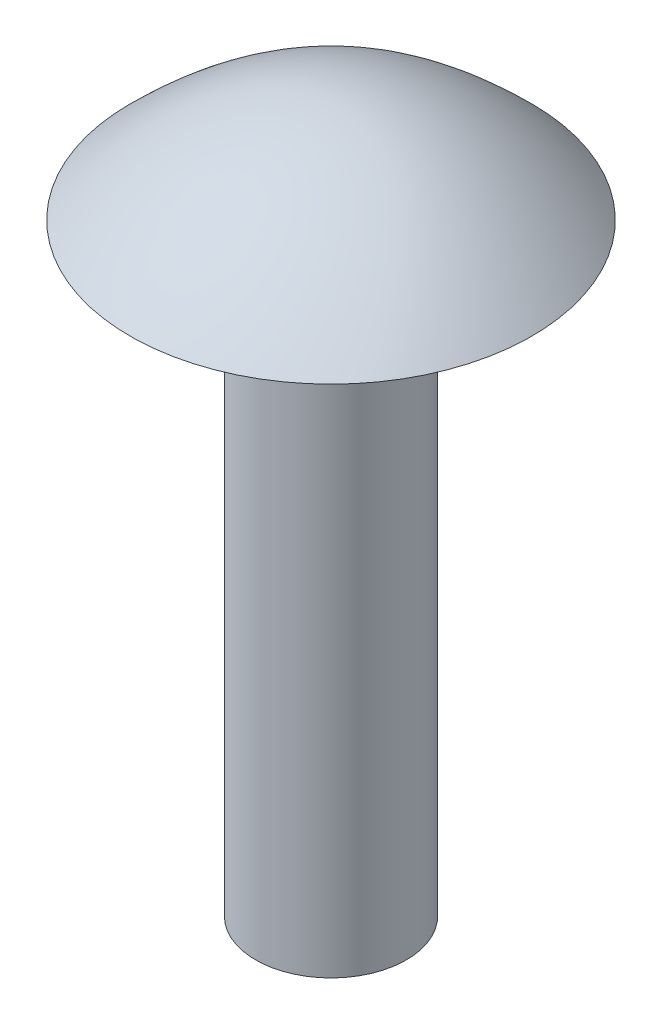
SolidWorks part; units mm, degrees
ref_plane "Front Plane" through (0, 0, 0) normal (0, 0, 1) x (1, 0, 0)
ref_plane "Top Plane" through (0, 0, 0) normal (0, 1, 0) x (1, 0, 0)
ref_plane "Right Plane" through (0, 0, 0) normal (1, 0, 0) x (0, 0, -1)
sketch "Sketch1" plane through (0, 0, 0) normal (0, 0, 1) x (1, 0, 0)
  line L0 (0, 0) -> (0, 6)
  line L1 (0, 0) -> (0.75, 0)
  line L2 (0, 6) -> (-1.25, 6)
  line L3 (0.75, -1.4044) -> (0.75, 9.5529) construction
  line L4 (0.75, 0) -> (0.75, 7)
  spline S0 degree 2 poles (-1.25, 6) (-0.25, 7) (0.75, 7) knots 0 0 0 0.5 0.5 0.5
revolve "Revolve1" add sketch "Sketch1" angle 360 about L3
